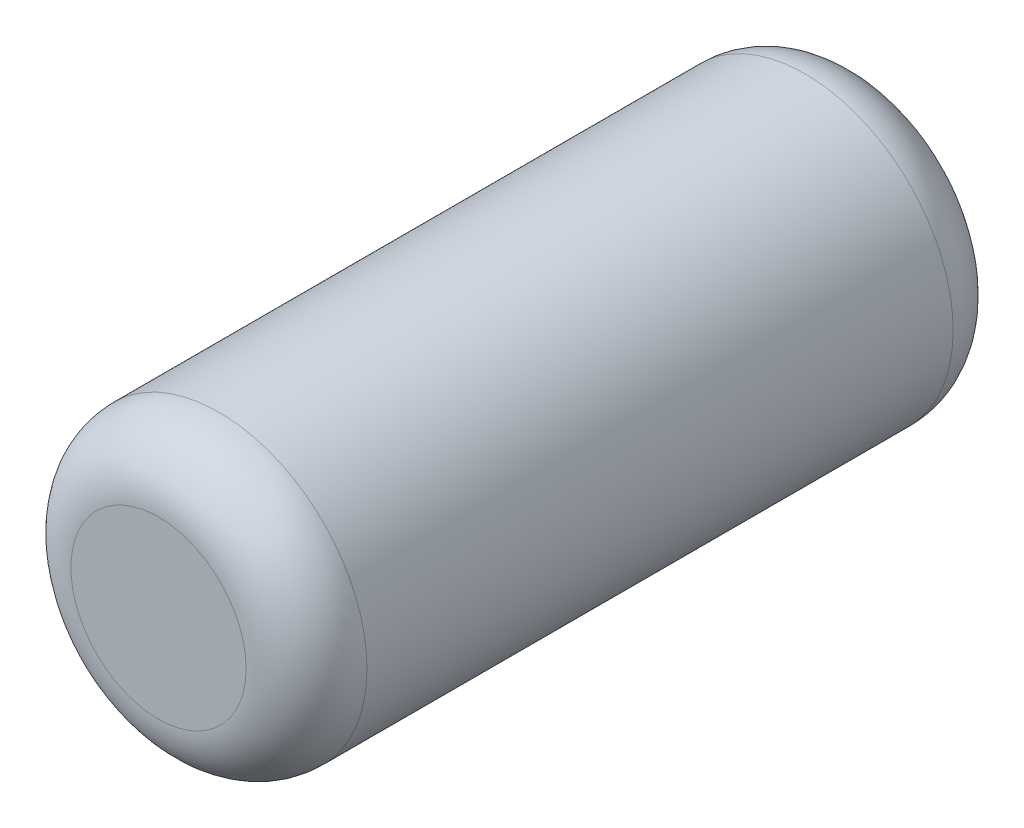
SolidWorks part; units mm, degrees
ref_plane "Front Plane" through (0, 0, 0) normal (0, 0, 1) x (1, 0, 0)
ref_plane "Top Plane" through (0, 0, 0) normal (0, 1, 0) x (1, 0, 0)
ref_plane "Right Plane" through (0, 0, 0) normal (1, 0, 0) x (0, 0, -1)
sketch "Sketch1" plane through (0, 0, 0) normal (0, 0, 1) x (1, 0, 0)
  circle A0 centre (0, 0) radius 49
  dimension "D1" = 98
extrude "Boss-Extrude1" add sketch "Sketch1" along normal mid plane 234
fillet "Fillet1" radius 20 2 edges at (49, 0, 117) (49, 0, -117)
